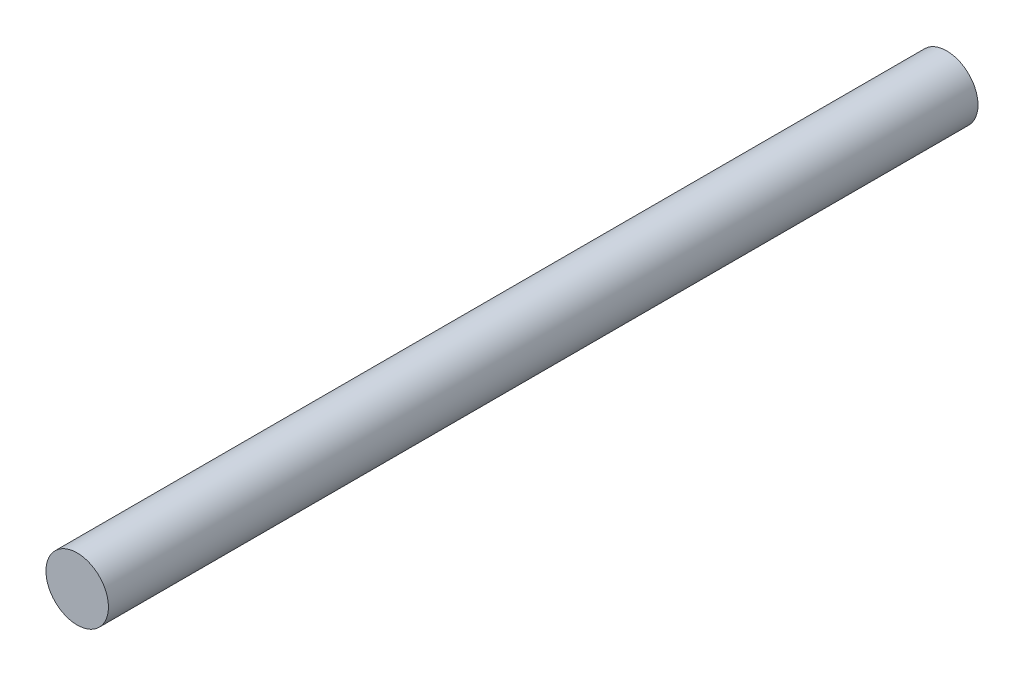
SolidWorks part; units mm, degrees
ref_plane "Front Plane" through (0, 0, 0) normal (0, 0, 1) x (1, 0, 0)
ref_plane "Top Plane" through (0, 0, 0) normal (0, 1, 0) x (1, 0, 0)
ref_plane "Right Plane" through (0, 0, 0) normal (1, 0, 0) x (0, 0, -1)
sketch "Sketch1" plane through (0, 0, 0) normal (0, 0, 1) x (1, 0, 0)
  line L0 (0, 0) -> (26.4208, 0) construction
  line L1 (0, 0) -> (0, 34.4793) construction
  circle A0 centre (0, 0) radius 2.875
  dimension "D1" = 5.75
extrude "Boss-Extrude1" add sketch "Sketch1" along normal blind 80
